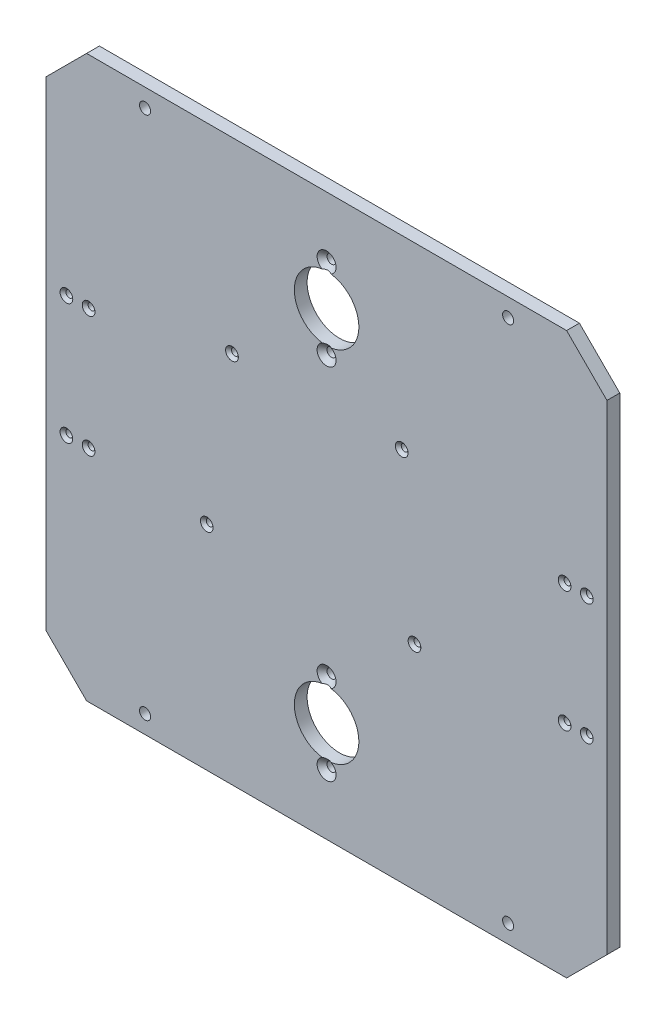
SolidWorks part; units mm, degrees
ref_plane "Front Plane" through (0, 0, 0) normal (0, 0, 1) x (1, 0, 0)
ref_plane "Top Plane" through (0, 0, 0) normal (0, 1, 0) x (1, 0, 0)
ref_plane "Right Plane" through (0, 0, 0) normal (1, 0, 0) x (0, 0, -1)
sketch "Sketch1" plane through (0, 0, 0) normal (0, 0, 1) x (1, 0, 0)
  line L0 (-79.0045, 0) -> (94.053, 0) construction
  line L1 (0, 67.0127) -> (0, -68.6587) construction
  line L3 (139, -139) -> (-139, -139)
  line L4 (139, -139) -> (139, 139)
  line L5 (139, 139) -> (-139, 139)
  line L6 (-139, -139) -> (-139, 139)
  line L7 (139, -139) -> (-139, 139) construction
  line L8 (139, 139) -> (-139, -139) construction
  point P4 (0, 0)
  dimension "D1" = 278
  dimension "D2" = 278
extrude "Boss-Extrude1" add sketch "Sketch1" along normal blind 6.35
chamfer "Chamfer1" distance 20 angle 45 4 edges at (139, -139, 3.175) (139, 139, 3.175) (-139, 139, 3.175) (-139, -139, 3.175)
sketch "Sketch4" plane through (0, 0, 6.35) normal (0, 0, 1) x (1, 0, 0)
  line L0 (0, 186.846) -> (0, -174.5938) construction
  line L1 (219.7737, 0) -> (-232.7917, 0) construction
  line L2 (119, 139) -> (-119, 139) construction
  line L3 (-90, 130) -> (90, 130) construction
  circle A0 centre (-90, 130) radius 2.75
  circle A1 centre (0, 151) radius 2.75
  circle A2 centre (90, 130) radius 2.75
  circle A3 centre (90, -130) radius 2.75
  circle A4 centre (0, -151) radius 2.75
  circle A5 centre (-90, -130) radius 2.75
  dimension "D1" = 5.5
  dimension "D2" = 9
  dimension "D3" = 90
extrude "Cut-Extrude2" cut sketch "Sketch4" against normal blind 76.2
sketch "Sketch8" plane through (0, 0, 6.35) normal (0, 0, 1) x (1, 0, 0)
  line L0 (0, 225.553) -> (0, -227.4564) construction
  line L1 (119, 139) -> (-119, 139) construction
  line L2 (139, 0) -> (-139, 0) construction
  line L3 (139, -119) -> (139, 119) construction
  line L4 (-139, 119) -> (-139, -119) construction
  circle A0 centre (0, 89) radius 16
  circle A1 centre (0, -89) radius 16
  dimension "D3" = 32
  dimension "D1" = 50
extrude "Cut-Extrude4" cut sketch "Sketch8" against normal blind 105
hole_wizard "CSK for M4 Flat Head Machine Screw2" positions "Sketch10" profile "Sketch9" countersink size "M4" standard "ANSI Metric" end condition through all
sketch "Sketch10" plane through (0, 0, 6.35) normal (0, 0, 1) x (1, 0, 0)
  line L5 (0, 205.0159) -> (0, -212.7914) construction
  line L6 (16, 89) -> (-16, 89) construction
  line L8 (156.7583, 0) -> (-175.5166, 0) construction
  line L9 (-16, 89) -> (16, 89) construction
  circle A1 centre (0, 89) radius 16 construction
  point P4 (0, 109)
  point P55 (0, 69)
  point P60 (0, -69)
  point P61 (0, -109)
  dimension "D1" = 40
  dimension "D2" = 20
sketch "Sketch9" plane through (0, 109, 6.35) normal (1, 0, 0) x (0, -1, 0)
  line L0 (0, 0) -> (0, 6.35)
  line L1 (0, 6.35) -> (2.25, 6.35)
  line L2 (2.25, 6.35) -> (2.25, 2.45)
  line L3 (2.25, 2.45) -> (4.7, 0)
  line L5 (4.7, 0) -> (0, 0)
  line L6 (-2.25, 2.45) -> (-4.7, 0) construction
  line L11 (0, -6.35) -> (0, 107.95) construction
  dimension "Thru Hole Dia." = 4.5
  dimension "Thru Hole Depth" = 6.35
  dimension "Near C'Sink Dia." = 9.4
  dimension "Near C'Sink Angle" = 90
hole_wizard "CSK for M3 Flat Head Machine Screw1" positions "Sketch12" profile "Sketch11" countersink size "M3" standard "ANSI Metric" end condition through all
sketch "Sketch12" plane through (0, 0, 6.35) normal (0, 0, 1) x (1, 0, 0)
  line L0 (0, 139) -> (0, -139) construction
  line L1 (119, 139) -> (-119, 139) construction
  line L2 (-119, -139) -> (119, -139) construction
  line L4 (-139, 0) -> (139, 0) construction
  line L5 (-139, 119) -> (-139, -119) construction
  line L6 (139, -119) -> (139, 119) construction
  point P0 (-129, 30)
  point P2 (-118, 30)
  point P24 (-118, -30)
  point P25 (-129, -30)
  point P26 (129, -30)
  point P27 (118, -30)
  point P28 (118, 30)
  point P29 (129, 30)
  dimension "D1" = 11
  dimension "D2" = 60
  dimension "D3" = 10
sketch "Sketch11" plane through (-129, 30, 6.35) normal (1, 0, 0) x (0, -1, 0)
  line L0 (0, 0) -> (0, 6.35)
  line L1 (0, 6.35) -> (1.7, 6.35)
  line L2 (1.7, 6.35) -> (1.7, 1.45)
  line L3 (1.7, 1.45) -> (3.15, 0)
  line L5 (3.15, 0) -> (0, 0)
  line L6 (-1.7, 1.45) -> (-3.15, 0) construction
  line L11 (0, -6.35) -> (0, 107.95) construction
  dimension "Thru Hole Dia." = 3.4
  dimension "Thru Hole Depth" = 6.35
  dimension "Near C'Sink Dia." = 6.3
  dimension "Near C'Sink Angle" = 90
sketch "Sketch15" plane through (0, 0, 0) normal (0, 0, 1) x (1, 0, 0)
  point P0 (37.2502, 47.0668)
  point P1 (43.5842, -33.39)
  point P10 (-46.9158, 46.11)
  point P14 (-59.4158, -33.39)
hole_wizard "CSK for M3 Flat Head Machine Screw2" positions "Sketch21" profile "Sketch20" countersink size "M3" standard "ANSI Metric" end condition through all
sketch "Sketch21" plane through (0, 0, 6.35) normal (0, 0, 1) x (1, 0, 0)
  point P0 (-46.9158, 46.11)
sketch "Sketch20" plane through (-46.9158, 46.11, 6.35) normal (1, 0, 0) x (0, -1, 0)
  line L0 (0, 0) -> (0, 6.35)
  line L1 (0, 6.35) -> (1.7, 6.35)
  line L2 (1.7, 6.35) -> (1.7, 1.45)
  line L3 (1.7, 1.45) -> (3.15, 0)
  line L5 (3.15, 0) -> (0, 0)
  line L6 (-1.7, 1.45) -> (-3.15, 0) construction
  line L11 (0, -6.35) -> (0, 107.95) construction
  dimension "Thru Hole Dia." = 3.4
  dimension "Thru Hole Depth" = 6.35
  dimension "Near C'Sink Dia." = 6.3
  dimension "Near C'Sink Angle" = 90
pattern_sketch "Sketch-Pattern1" of "CSK for M3 Flat Head Machine Screw2" driven by "Sketch15"
equation "\"plate_thickness\" = 6.35 'thickness of the plate "
equation "\"height\"= 180"
equation "\"D1@Boss-Extrude1\"=\"plate_thickness\""
equation "\"t_height\" = 200"
equation "\"t_width\" = 240"
equation "\"t_length\" = 240"
equation "\"plate_spacing\" = 1"
equation "\"front_plate_height\" = \"t_height\" + 38"
equation "\"front_plate_width\" = \"t_width\" + 38"
equation "\"side_plate_height\" = \"front_plate_height\""
equation "\"side_plate_length\" = \"t_length\" + 38"
equation "\"top_plate_width\" = \"front_plate_width\""
equation "\"top_plate_length\" = \"side_plate_length\""
equation "\"D2@Sketch1\"=\"top_plate_width\""
equation "\"D1@Sketch1\"=\"top_plate_length\""
equation "\"plate_hole_spacing\"= 9"
equation "\"connector_D1\" = 70 'the big holes diameter"
equation "\"connector_mtg_D2\"= 5.5 'mounting holes"
equation "\"mtg_dfc\" = 40 'mounting hole distance from center"
equation "\"mtg_hole_D\" = 5.5 'mounting holes"
equation "\"plate_hole_from_edge\" = 9"
equation "\"D1@Sketch4\"=\"mtg_hole_D\""
equation "\"D2@Sketch4\"=\"plate_hole_from_edge\""
equation "\"itx_support_t_slot_length\" = \"t_width\" + (2 * 20.5)"
equation "\"locomotion_length\" = \"t_length\""
equation "\"locomotion_width\" = \"t_width\""
equation "\"locomotion_height\" = 40"
equation "\"itx_mtg_hole_spacing\" = 40"
equation "\"emg30_bracket_hole_len\" = 60"
equation "\"emg30_bracket_hole_wid\" = 11"
equation "\"D2@Sketch12\"=\"emg30_bracket_hole_len\""
equation "\"D1@Sketch12\"=\"emg30_bracket_hole_wid\""
equation "\"D2@Sketch10\"=\"D1@Sketch10\"*.5"
